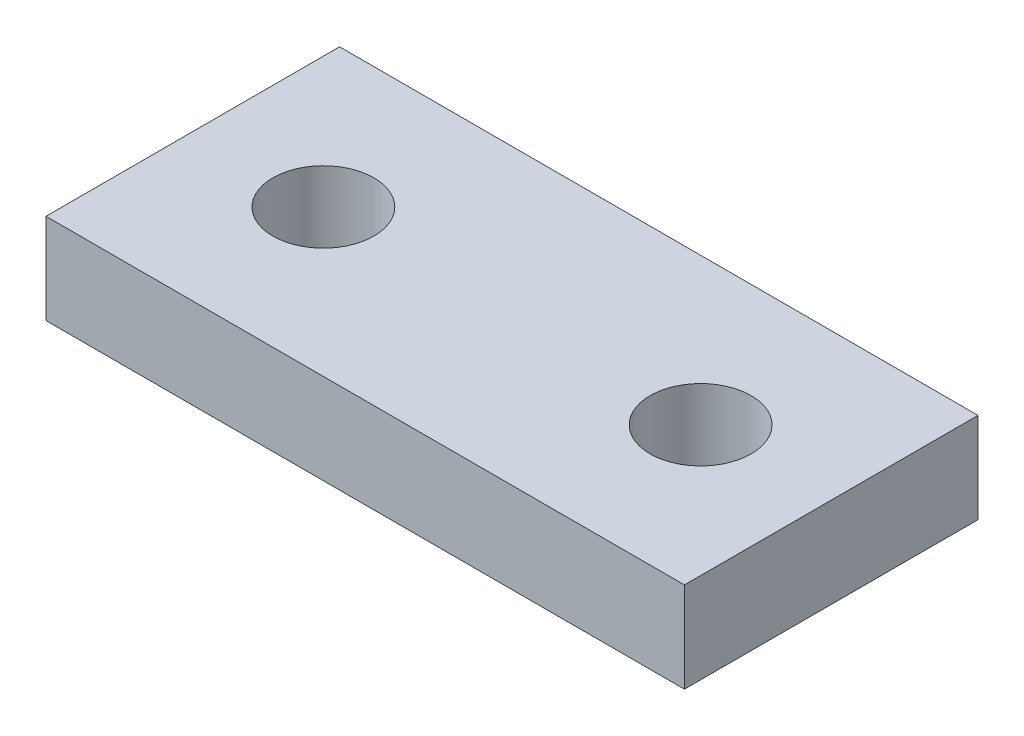
SolidWorks part; units mm, degrees
ref_plane "Front Plane" through (0, 0, 0) normal (0, 0, 1) x (1, 0, 0)
ref_plane "Top Plane" through (0, 0, 0) normal (0, 1, 0) x (1, 0, 0)
ref_plane "Right Plane" through (0, 0, 0) normal (1, 0, 0) x (0, 0, -1)
sketch "Sketch1" plane through (0, 0, 0) normal (0, 1, 0) x (1, 0, 0)
  line L1 (-134.6504, 61.9168) -> (134.6504, 61.9168)
  line L2 (-134.6504, 61.9168) -> (-134.6504, -61.9168)
  line L3 (-134.6504, -61.9168) -> (134.6504, -61.9168)
  line L4 (134.6504, 61.9168) -> (134.6504, -61.9168)
  point P0 (0, 0)
extrude "Boss-Extrude1" add sketch "Sketch1" along normal blind 38.1
sketch "Sketch2" plane through (0, 38.1, 0) normal (0, 1, 0) x (1, 0, 0)
  circle A0 centre (-79.5623, 0) radius 21.3083
extrude "Cut-Extrude1" cut sketch "Sketch2" against normal blind 38.1
ref_plane "Plane1" through (0, 0, 0) normal (1, 0, 0) x (0, 0, -1)
mirror "Mirror1" about plane through (0, 0, 0) normal (1, 0, 0) of "Cut-Extrude1"
